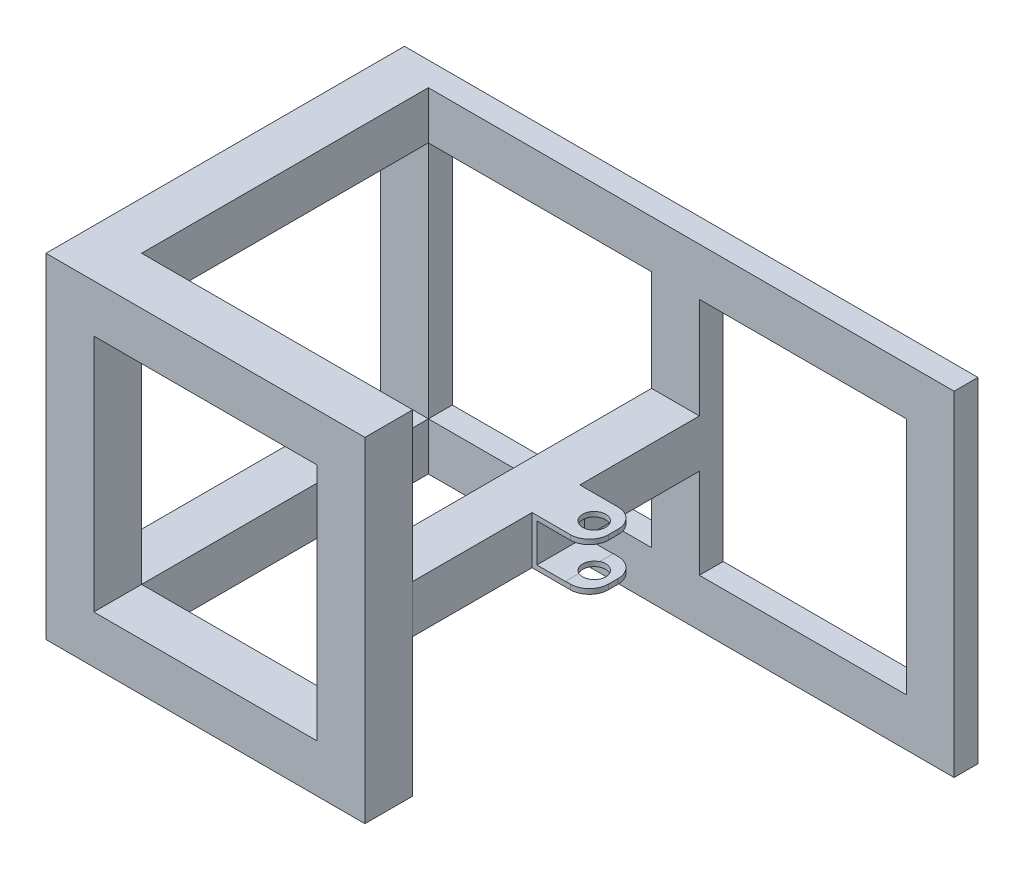
SolidWorks part; units mm, degrees
ref_plane "Front Plane" through (0, 0, 0) normal (0, 0, 1) x (1, 0, 0)
ref_plane "Top Plane" through (0, 0, 0) normal (0, 1, 0) x (1, 0, 0)
ref_plane "Right Plane" through (0, 0, 0) normal (1, 0, 0) x (0, 0, -1)
sketch "Sketch1" plane through (0, 0, 0) normal (0, 0, 1) x (1, 0, 0)
  line L0 (-50, 300) -> (550, 300)
  line L1 (0, 0) -> (500, 0)
  line L2 (0, 0) -> (0, 250)
  line L3 (0, 250) -> (500, 250)
  line L4 (500, 0) -> (500, 250)
  line L5 (550, -50) -> (550, 300)
  line L6 (-50, -50) -> (550, -50)
  line L7 (-50, -50) -> (-50, 300)
  dimension "D1" = 250
  dimension "D2" = 500
  dimension "D3" = 50
extrude "Boss-Extrude1" add sketch "Sketch1" along normal blind 25
sketch "Sketch2" plane through (0, 0, 25) normal (0, 0, 1) x (1, 0, 0)
  line L1 (-50, 300) -> (0, 300)
  line L2 (-50, 300) -> (-50, 250)
  line L3 (-50, 250) -> (0, 250)
  line L4 (0, 300) -> (0, 250)
  line L5 (0, 0) -> (-50, 0)
  line L6 (0, 0) -> (0, -50)
  line L7 (0, -50) -> (-50, -50)
  line L8 (-50, 0) -> (-50, -50)
extrude "Boss-Extrude2" add sketch "Sketch2" along normal blind 350
sketch "Sketch6" plane through (0, 250, 0) normal (0, -1, 0) x (1, 0, 0)
  line L4 (233.4833, 0) -> (283.4833, 0)
  line L5 (233.4833, 0) -> (233.4833, 25)
  line L6 (233.4833, 25) -> (283.4833, 25)
  line L7 (283.4833, 0) -> (283.4833, 25)
  point P8 (250, 12.5)
  dimension "D1" = 25
  dimension "D2" = 50
extrude "Boss-Extrude5" add sketch "Sketch6" along normal blind 300
sketch "Sketch7" plane through (0, 0, 25) normal (0, 0, 1) x (1, 0, 0)
  line L0 (233.4833, 250) -> (233.4833, 0)
  line L2 (283.4833, 0) -> (283.4833, 250) construction
  line L4 (233.4833, 94.3366) -> (283.4833, 94.3366)
  line L5 (233.4833, 94.3366) -> (233.4833, 144.3366)
  line L6 (233.4833, 144.3366) -> (283.4833, 144.3366)
  line L7 (283.4833, 94.3366) -> (283.4833, 144.3366)
  point P8 (258.4833, 125)
  line M7 (283.4833, 0) -> (283.4833, 250)
  dimension "D1" = 50
  dimension "D2" = 50
extrude "Boss-Extrude6" add sketch "Sketch7" along normal blind 300 contours L6 L0 L4 M7
sketch "Sketch8" plane through (0, 0, 325) normal (0, 0, 1) x (1, 0, 0)
  line L1 (233.4833, 144.3366) -> (283.4833, 144.3366)
  line L2 (233.4833, 144.3366) -> (233.4833, 94.3366)
  line L3 (233.4833, 94.3366) -> (283.4833, 94.3366)
  line L4 (283.4833, 144.3366) -> (283.4833, 94.3366)
extrude "Boss-Extrude7" add sketch "Sketch8" along normal blind 50
sketch "Sketch9" plane through (0, 0, 375) normal (0, 0, 1) x (1, 0, 0)
  line L0 (550, 300) -> (0, 300) construction
  line L1 (-50, -50) -> (283.6499, -50)
  line L2 (-50, -50) -> (-50, 300)
  line L3 (-50, 300) -> (283.6499, 300)
  line L4 (283.6499, -50) -> (283.6499, 300)
  line L6 (0, 0) -> (233.4833, 0)
  line L7 (0, 0) -> (0, 250)
  line L8 (0, 250) -> (233.4833, 250)
  line L9 (233.4833, 0) -> (233.4833, 250)
extrude "Boss-Extrude8" add sketch "Sketch9" against normal blind 50
sketch "Sketch10" plane through (283.4833, 0, 0) normal (1, 0, 0) x (0, 0, -1)
  line L3 (-325, 144.3366) -> (-25, 144.3366) construction
  line L4 (-200, 94.3366) -> (-150, 94.3366)
  line L5 (-200, 94.3366) -> (-200, 144.3366)
  line L6 (-200, 144.3366) -> (-150, 144.3366)
  line L7 (-150, 94.3366) -> (-150, 144.3366)
  point P6 (-175, 119.3366)
  dimension "D1" = 50
extrude "Boss-Extrude10" add sketch "Sketch10" along normal blind 10
sketch "Sketch12" plane through (0, 94.3366, 0) normal (0, -1, 0) x (1, 0, 0)
  line L1 (293.4833, 150) -> (323.4833, 150)
  line L2 (293.4833, 150) -> (293.4833, 200)
  line L3 (293.4833, 200) -> (323.4833, 200)
  line L4 (343.4833, 170) -> (343.4833, 180)
  arc A0 (343.4833, 170) -> (323.4833, 150) centre (323.4833, 170) cw
  arc A1 (343.4833, 180) -> (323.4833, 200) centre (323.4833, 180) ccw
  point P7 (343.4833, 150)
  point P10 (343.4833, 200)
  dimension "D3" = 20
  dimension "D1" = 50
  dimension "D2" = 50
extrude "Boss-Extrude13" add sketch "Sketch12" against normal blind 50
sketch "Sketch15" plane through (0, 0, 200) normal (0, 0, 1) x (1, 0, 0)
  line L0 (288.4833, 139.3366) -> (318.4833, 139.3366)
  line L1 (283.4833, 144.3366) -> (323.4833, 144.3366)
  line L2 (283.4833, 144.3366) -> (283.4833, 94.3366)
  line L3 (283.4833, 94.3366) -> (323.4833, 94.3366)
  line L4 (323.4833, 144.3366) -> (323.4833, 94.3366)
  line L5 (318.4833, 139.3366) -> (318.4833, 99.3366)
  line L6 (288.4833, 99.3366) -> (318.4833, 99.3366)
  line L7 (288.4833, 139.3366) -> (288.4833, 99.3366)
  dimension "D1" = 5
extrude "Cut-Extrude1" cut sketch "Sketch15" against normal blind 50 contours L0 L5 L6 L7
sketch "Sketch16" plane through (0, 94.3366, 0) normal (0, -1, 0) x (1, 0, 0)
  circle A0 centre (323.4833, 175) radius 12
extrude "Cut-Extrude2" cut sketch "Sketch16" against normal blind 50
sketch "Sketch17" plane through (288.4833, 0, 0) normal (1, 0, 0) x (0, 0, -1)
  line L0 (-200, 144.3366) -> (-200, 94.3366) construction
  line L1 (-150.9763, 138.0442) -> (-200, 138.0442)
  line L2 (-150.9763, 138.0442) -> (-150.9763, 101.5205)
  line L3 (-150.9763, 101.5205) -> (-200, 101.5205)
  line L4 (-200, 138.0442) -> (-200, 101.5205)
extrude "Cut-Extrude3" cut sketch "Sketch17" along normal blind 100
sketch "Sketch18" plane through (0, 0, 200) normal (0, 0, 1) x (1, 0, 0)
  line L1 (288.4833, 139.3366) -> (346.0786, 139.3366)
  line L2 (288.4833, 139.3366) -> (288.4833, 99.5408)
  line L3 (288.4833, 99.5408) -> (346.0786, 99.5408)
  line L4 (346.0786, 139.3366) -> (346.0786, 99.5408)
extrude "Cut-Extrude4" cut sketch "Sketch18" against normal blind 100
